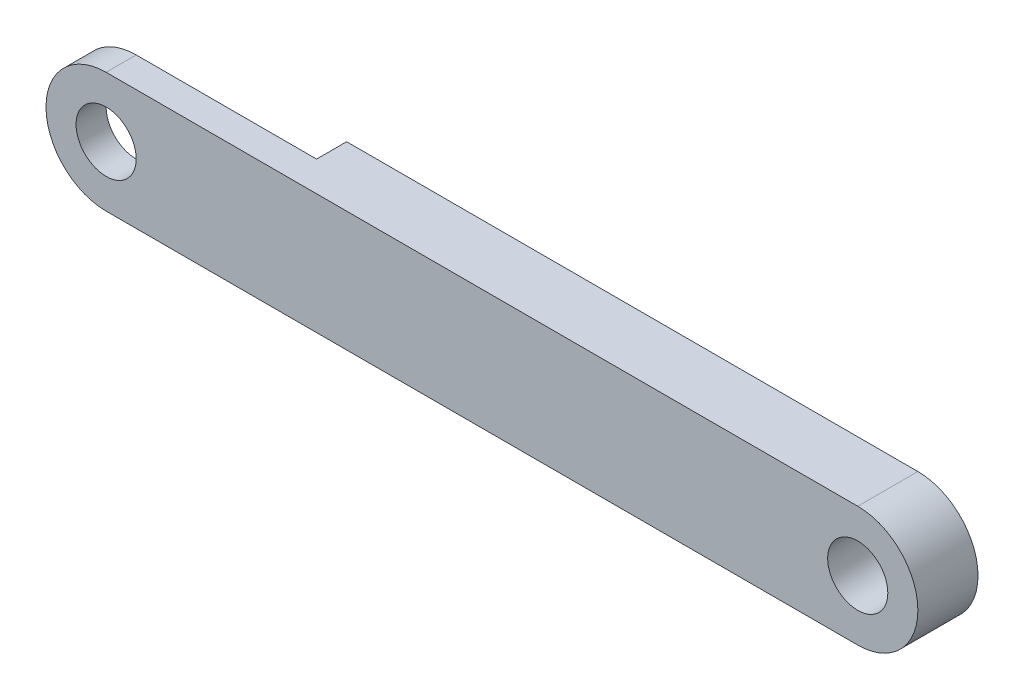
SolidWorks part; units mm, degrees
ref_plane "Front Plane" through (0, 0, 0) normal (0, 0, 1) x (1, 0, 0)
ref_plane "Top Plane" through (0, 0, 0) normal (0, 1, 0) x (1, 0, 0)
ref_plane "Right Plane" through (0, 0, 0) normal (1, 0, 0) x (0, 0, -1)
sketch "Sketch1" plane through (0, 0, 0) normal (0, 0, 1) x (1, 0, 0)
  line L0 (0, 0) -> (125, 0) construction
  line L1 (0, 10) -> (125, 10)
  line L2 (0, -10) -> (125, -10)
  circle A0 centre (0, 0) radius 5
  arc A1 (0, 10) -> (0, -10) centre (0, 0) ccw
  arc A2 (125, -10) -> (125, 10) centre (125, 0) ccw
  circle A3 centre (125, 0) radius 5
  point P3 (62.5, 0)
  dimension "D1" = 10
  dimension "D3" = 10
  dimension "D4" = 10
  dimension "D2" = 125
extrude "Boss-Extrude1" add sketch "Sketch1" along normal mid plane 10
sketch "Sketch2" plane through (0, 0, 0) normal (0, 0, 1) x (1, 0, 0)
  line L0 (125, 10) -> (0, 10) construction
  line L1 (-29.4028, -10) -> (30, -10)
  line L2 (-29.4028, -10) -> (-29.4028, 10)
  line L3 (-29.4028, 10) -> (30, 10)
  line L4 (30, -10) -> (30, 10)
  point P0 (0, 0)
  dimension "D1" = 30
  dimension "D2" = 20
extrude "Cut-Extrude1" cut sketch "Sketch2" against normal through all
